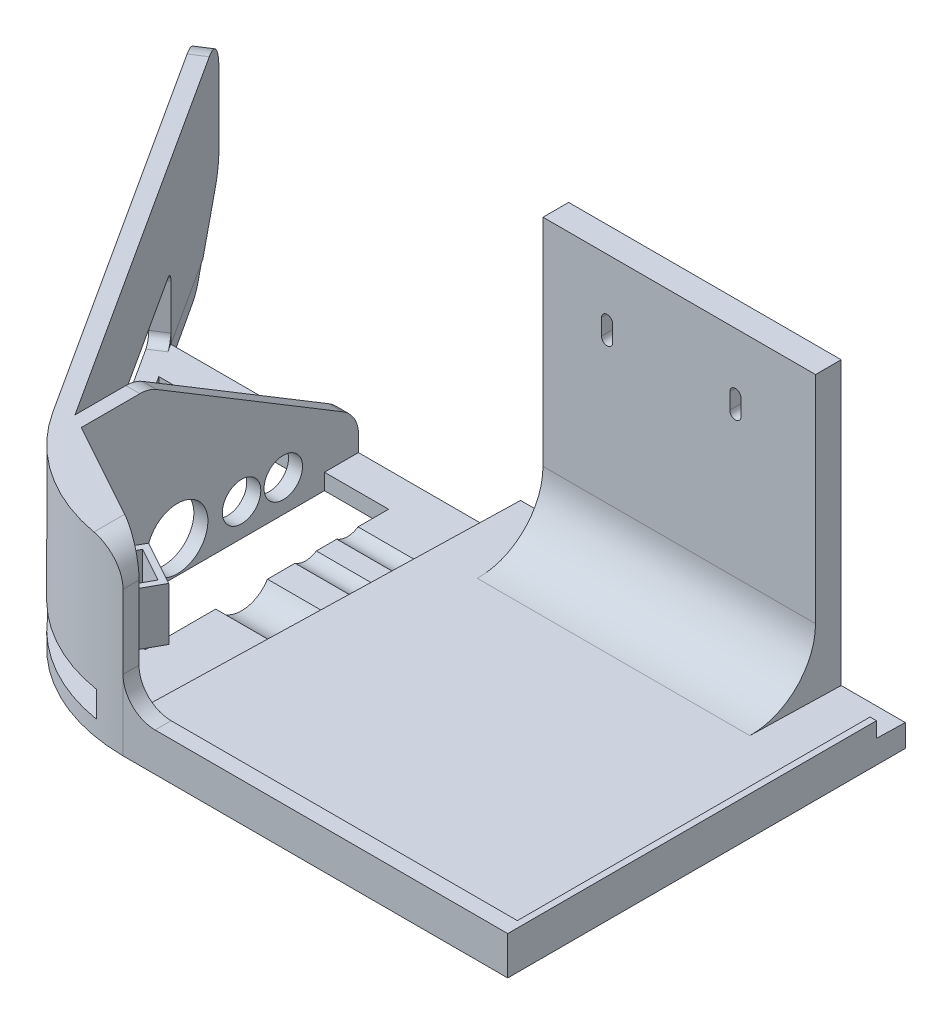
SolidWorks part; units mm, degrees
ref_plane "Front Plane" through (0, 0, 0) normal (0, 0, 1) x (1, 0, 0)
ref_plane "Top Plane" through (0, 0, 0) normal (0, 1, 0) x (1, 0, 0)
ref_plane "Right Plane" through (0, 0, 0) normal (1, 0, 0) x (0, 0, -1)
sketch "Sketch1" plane through (0, 0, 0) normal (0, 1, 0) x (1, 0, 0)
  line L0 (-48.7821, 26.8903) -> (-130, 153)
  line L1 (0, 0) -> (155, 0)
  line L2 (0, 0) -> (0, 5)
  line L3 (0, 5) -> (155, 5)
  line L4 (155, 0) -> (155, 5)
  line L5 (-130, 153) -> (-125.7963, 155.7073)
  line L6 (-125.7963, 155.7073) -> (-44.5785, 29.5976)
  line L7 (-44.5785, 29.5976) -> (-48.7821, 26.8903)
  line L8 (-44.5785, 29.5976) -> (0, 5)
  line L9 (-44.5785, 29.5976) -> (-48.7821, 26.8903)
  line L10 (0, 5) -> (0, 0)
  arc A0 (0, 0) -> (-48.7821, 26.8903) centre (0.3966, 58.4127) cw
  dimension "D1" = 130
  dimension "D3" = 150
  dimension "D4" = 58.4141
  dimension "D2" = 153
  dimension "D5" = 90
  dimension "D6" = 0
  dimension "D7" = 150
  dimension "D8" = 155
  dimension "D9" = 5
  dimension "D10" = 5
extrude "Boss-Extrude2" add sketch "Sketch1" along normal blind 55 contours L7 L6 L5 L0 | A0 L2 L8 L7 | L1 L4 L3 L2
sketch "Sketch2" plane through (0, 0, 0) normal (0, 0, 1) x (1, 0, 0)
  line L0 (0, 0) -> (155, 0) construction
  line L1 (155, 55) -> (43, 55)
  line L2 (155, 55) -> (155, 10)
  line L3 (155, 10) -> (43, 10)
  line L4 (43, 55) -> (43, 10)
  line L5 (5, 50) -> (35, 50)
  line L6 (5, 50) -> (5, 25)
  line L7 (5, 25) -> (35, 25)
  line L8 (35, 50) -> (35, 25)
  line L9 (0, 55) -> (0, 0) construction
  circle A0 centre (5, 50) radius 1.75
  circle A1 centre (35, 50) radius 1.75
  circle A2 centre (5, 25) radius 1.75
  circle A3 centre (35, 25) radius 1.75
  line M10 (155, 0) -> (155, 55)
  line M11 (155, 55) -> (0, 55)
  dimension "D6" = 3.5
  dimension "D7" = 3.5
  dimension "D8" = 3.5
  dimension "D9" = 3.5
  dimension "D2" = 25
  dimension "D3" = 25
  dimension "D4" = 30
  dimension "D5" = 5
  dimension "D10" = 10
  dimension "D11" = 8
  dimension "D12" = 8
extrude "Cut-Extrude1" cut sketch "Sketch2" against normal blind 55 contours L4 L3 M11 M10 | A2 | A0 | A1 | A3
sketch "Sketch3" plane through (-22.2397, 0, 14.3229) normal (-0.8407, 0, 0.5415) x (0.5415, 0, 0.8407)
  line L0 (-49.0207, 55) -> (-49.0207, 0) construction
  line L1 (-49.0207, 25) -> (-149.0207, 25)
  line L2 (-49.0207, 25) -> (-49.0207, 5)
  line L3 (-49.0207, 5) -> (-149.0207, 5)
  line L4 (-149.0207, 25) -> (-149.0207, 5)
  line L5 (-49.0207, 0) -> (-199.0207, 0) construction
  dimension "D1" = 5
  dimension "D2" = 20
  dimension "D3" = 100
extrude "Cut-Extrude2" cut sketch "Sketch3" against normal blind 55
sketch "Sketch4" plane through (2.115, 0, -3.833) normal (0.4831, 0, -0.8756) x (-0.8756, 0, -0.4831)
  line L6 (53.33, 25) -> (53.33, 5) construction
  line L11 (53.33, 0) -> (2.4156, 0) construction
  line L12 (8.33, 13.0659) -> (48.33, 13.0659)
  line L13 (8.33, 13.0659) -> (8.33, 5)
  line L14 (8.33, 5) -> (48.33, 5)
  line L15 (48.33, 13.0659) -> (48.33, 5)
  dimension "D1" = 5
  dimension "D2" = 40
  dimension "D3" = 5
extrude "Cut-Extrude3" cut sketch "Sketch4" against normal blind 55
sketch "Sketch5" plane through (0, 0, 0) normal (0, -1, 0) x (1, 0, 0)
  line L0 (0, -5) -> (-44.5785, -29.5976)
  line L2 (0, -5) -> (0, -155.7073)
  line L3 (0, -155.7073) -> (-125.7963, -155.7073)
  line L5 (-44.5785, -29.5976) -> (0, -5) construction
  line L6 (-44.5785, -29.5976) -> (-125.7963, -155.7073)
extrude "Boss-Extrude4" add sketch "Sketch5" against normal blind 5
sketch "Sketch8" plane through (0, 5, 0) normal (0, 1, 0) x (1, 0, 0)
  line L5 (-44.5785, 29.5976) -> (-98.7237, 113.6707)
  line L7 (-44.5785, 29.5976) -> (-44.5785, 113.6707)
  line L8 (-44.5785, 113.6707) -> (-98.7237, 113.6707)
extrude "Cut-Extrude4" cut sketch "Sketch8" against normal blind 50
sketch "Sketch9" plane through (0, 5, 0) normal (0, 1, 0) x (1, 0, 0)
  line L1 (-40.2007, 27.182) -> (-44.5785, 27.182)
  line L2 (-40.2007, 27.182) -> (-40.2007, 113.6707)
  line L3 (-40.2007, 113.6707) -> (-44.5785, 113.6707)
  line L4 (-44.5785, 27.182) -> (-44.5785, 113.6707)
extrude "Boss-Extrude7" add sketch "Sketch9" along normal blind 50
sketch "Sketch10" plane through (0, 5, 0) normal (0, 1, 0) x (1, 0, 0)
  line L1 (-40.2007, 113.6707) -> (-20.2007, 113.6707)
  line L2 (-40.2007, 113.6707) -> (-40.2007, 27.1384)
  line L3 (-40.2007, 27.1384) -> (-20.2007, 27.1384)
  line L4 (-20.2007, 113.6707) -> (-20.2007, 27.1384)
  dimension "D1" = 20
extrude "Cut-Extrude5" cut sketch "Sketch10" against normal blind 10
sketch "Sketch12" plane through (-40.2007, 0, 0) normal (1, 0, 0) x (0, 0, -1)
  line L6 (27.182, 5) -> (27.182, 13.0659) construction
  circle A0 centre (57.182, 10) radius 9.5
  circle A1 centre (77.182, 10) radius 6
  dimension "D4" = 19
  dimension "D5" = 12
  dimension "D1" = 30
  dimension "D3" = 20
extrude "Cut-Extrude6" cut sketch "Sketch12" against normal blind 10
sketch "Sketch13" plane through (-40.2007, 0, 0) normal (1, 0, 0) x (0, 0, -1)
  circle A0 centre (57.182, 10) radius 9.5
  circle A1 centre (77.182, 10) radius 6
  circle A2 centre (57.182, 10) radius 9.5 construction
  circle A3 centre (77.182, 10) radius 6 construction
  dimension "D1" = 0
  dimension "D2" = 0
  dimension "D3" = 19
  dimension "D4" = 12
extrude "Cut-Extrude7" cut sketch "Sketch13" along normal blind 50
sketch "Sketch14" plane through (0, 5, 0) normal (0, 1, 0) x (1, 0, 0)
  line L0 (0, 103.0381) -> (-91.876, 103.0381)
  line L1 (0, 155.7073) -> (-126.1063, 155.7073)
  line L2 (0, 155.7073) -> (0, 103.0381)
  line L5 (-98.7237, 113.6707) -> (-125.7963, 155.7073) construction
  line L6 (-91.876, 103.0381) -> (-126.1063, 155.7073)
extrude "Cut-Extrude8" cut sketch "Sketch14" against normal blind 50
sketch "Sketch15" plane through (-22.2397, 0, 14.3229) normal (-0.8407, 0, 0.5415) x (0.5415, 0, 0.8407)
  line L0 (-176.0359, 0) -> (-199.0207, 18.2475)
  line L1 (-199.0207, 0) -> (-176.0359, 0)
  line L2 (-199.0207, 0) -> (-199.0207, 18.2475)
extrude "Cut-Extrude9" cut sketch "Sketch15" against normal blind 50
sketch "Sketch16" plane through (-40.2007, 0, 0) normal (1, 0, 0) x (0, 0, -1)
  line L0 (113.6707, 15.4952) -> (48.2529, 55)
  line L1 (113.6707, 55) -> (113.6707, 5) construction
  line L2 (27.182, 55) -> (113.6707, 55) construction
  line L3 (48.2529, 55) -> (113.6707, 55)
  line L4 (113.6707, 55) -> (113.6707, 15.4952)
extrude "Cut-Extrude10" cut sketch "Sketch16" against normal blind 10
fillet "Fillet5" radius 3 4 edges at (-100.8476, 5, -112.3029) (-46.6803, 5, -28.2439) (-100.8255, 25, -112.3171) (-46.6803, 25, -28.2439)
sketch "Sketch18" plane through (0, 5, 0) normal (0, 1, 0) x (1, 0, 0)
  line L1 (0, 103.0381) -> (-98.7678, 103.0381)
  line L2 (0, 103.0381) -> (0, 113.6423)
  line L3 (0, 113.6423) -> (-98.7678, 113.6423)
  line L4 (-98.7678, 103.0381) -> (-98.7678, 113.6423)
extrude "Boss-Extrude8" add sketch "Sketch18" against normal blind 5
sketch "Sketch19" plane through (0, 0, 0) normal (0, -1, 0) x (1, 0, 0)
  line L0 (-97.8232, -103.0381) -> (-98.7678, -104.5048)
  line L5 (-98.7678, -104.5048) -> (-98.7678, -103.0381)
  line L6 (-98.7678, -104.5048) -> (-98.7678, -103.0381) construction
  line L7 (-98.7678, -103.0381) -> (-97.8232, -103.0381)
extrude "Cut-Extrude11" cut sketch "Sketch19" against normal blind 5 contours L0 L5 L7
sketch "Sketch20" plane through (0, 0, 0) normal (0, -1, 0) x (1, 0, 0)
  line L1 (0, -5) -> (155, -5)
  line L2 (0, -5) -> (0, -124)
  line L3 (0, -124) -> (155, -124)
  line L4 (155, -5) -> (155, -124)
  dimension "D1" = 119
  dimension "D2" = 155
extrude "Boss-Extrude9" add sketch "Sketch20" against normal blind 10
sketch "Sketch21" plane through (155, 0, 0) normal (1, 0, 0) x (0, 0, -1)
  line L1 (124, 10) -> (0, 10) construction
  line L4 (5, 10) -> (124, 10)
  line L5 (124, 10) -> (124, 7)
  line L6 (124, 7) -> (5, 10)
  line L7 (124, 10) -> (124, 0) construction
  dimension "D1" = 5
  dimension "D2" = 0
  dimension "D3" = 3
extrude "Cut-Extrude13" cut sketch "Sketch21" against normal blind 155
sketch "Sketch24" plane through (0, 0, 0) normal (0, -1, 0) x (1, 0, 0)
  line L0 (0, -124) -> (155, -124) construction
  line L1 (125, -124) -> (15, -124)
  line L2 (125, -124) -> (125, -116)
  line L3 (125, -116) -> (15, -116)
  line L4 (15, -124) -> (15, -116)
  line L5 (155, 0) -> (155, -124) construction
  dimension "D1" = 30
  dimension "D2" = 110
  dimension "D3" = 8
extrude "Boss-Extrude10" add sketch "Sketch24" against normal blind 95
fillet "Fillet6" radius 20 1 edges at (70, 7.2017, -116)
sketch "Sketch25" plane through (0, 0, -124) normal (0, 0, -1) x (-1, 0, 0)
  line L0 (-33.25, 77) -> (-33.25, 72)
  line L6 (-125, 95) -> (-15, 95) construction
  line L10 (-36.75, 77) -> (-36.75, 72)
  line L11 (-73.25, 77) -> (-73.25, 72)
  line L12 (-76.75, 77) -> (-76.75, 72)
  line L13 (-15, 95) -> (-15, 27.7122) construction
  arc A4 (-36.75, 77) -> (-33.25, 77) centre (-35, 77) cw
  arc A5 (-73.25, 72) -> (-76.75, 72) centre (-75, 72) cw
  arc A6 (-73.25, 77) -> (-76.75, 77) centre (-75, 77) ccw
  arc A7 (-36.75, 72) -> (-33.25, 72) centre (-35, 72) ccw
  arc A8 (-33.25, 77) -> (-36.75, 77) centre (-35, 77) ccw
  point P11 (0, 0)
  dimension "D4" = 40
  dimension "D5" = 20
  dimension "D6" = 40
  dimension "D7" = 20
  dimension "D1" = 23
  dimension "D2" = 23
  dimension "D3" = 5
sketch "Sketch26" plane through (2.115, 0, -3.833) normal (0.4831, 0, -0.8756) x (-0.8756, 0, -0.4831)
  line L0 (48.33, 13.0659) -> (8.33, 13.0659) construction
  line L1 (36.33, 13.0659) -> (20.33, 13.0659)
  line L2 (36.33, 13.0659) -> (36.33, 14.5659)
  line L3 (36.33, 14.5659) -> (20.33, 14.5659)
  line L4 (20.33, 13.0659) -> (20.33, 14.5659)
  line L5 (8.33, 13.0659) -> (8.33, 5) construction
  line L6 (48.33, 55) -> (48.33, 13.0659) construction
  dimension "D1" = 12
  dimension "D2" = 12
  dimension "D3" = 16
  dimension "D4" = 1.5
extrude "Boss-Extrude11" add sketch "Sketch26" along normal blind 12
sketch "Sketch27" plane through (0, 14.5659, 0) normal (0, 1, 0) x (1, 0, 0)
  line L0 (-15.6851, 13.6547) -> (-9.8877, 24.1614)
  line L1 (-9.8877, 24.1614) -> (-23.8966, 31.8913)
  line L2 (-23.8966, 31.8913) -> (-29.694, 21.3846)
  line L3 (-29.694, 21.3846) -> (-28.0304, 20.4667)
  line L4 (-29.694, 21.3846) -> (-15.6851, 13.6547) construction
  line L5 (-28.0304, 20.4667) -> (-23.151, 29.3098)
  line L6 (-23.151, 29.3098) -> (-12.4692, 23.4158)
  line L7 (-12.4692, 23.4158) -> (-17.3486, 14.5727)
  line L8 (-17.3486, 14.5727) -> (-15.6851, 13.6547)
  dimension "D1" = 1.9
  dimension "D2" = 1.9
  dimension "D3" = 1.9
extrude "Boss-Extrude12" add sketch "Sketch27" along normal blind 15
sketch "Sketch28" plane through (0, 14.5659, 0) normal (0, 1, 0) x (1, 0, 0)
  circle A0 centre (-20.2498, 21.9412) radius 2.5
  dimension "D1" = 5
extrude "Cut-Extrude15" cut sketch "Sketch28" against normal blind 5
extrude "Cut-Extrude17" cut sketch "Sketch25" against normal blind 35 contours L10 A7 L0 A4 | L11 A6 L12 A5
sketch "Sketch29" plane through (0, 0, 0) normal (0, 0, 1) x (1, 0, 0)
  line L1 (43, 55) -> (0, 55)
  line L6 (0, 12) -> (43, 12)
  line L7 (0, 12) -> (0, 55)
  line L8 (43, 55) -> (43, 12)
extrude "Cut-Extrude18" cut sketch "Sketch29" against normal blind 35
fillet "Fillet9" radius 10 5 edges at (-127.8982, 55, -154.3536) (-115.5221, 0, -134.985) (-127.8982, 18.2475, -154.3536) (-42.3896, 15.4952, -113.6707) (-42.3896, 55, -48.2529)
sketch "Sketch31" plane through (155, 0, 0) normal (1, 0, 0) x (0, 0, -1)
  line L0 (124, 7) -> (124, 0) construction
  line L1 (0, 0) -> (124, 0)
  line L2 (0, 0) -> (0, 12)
  line L3 (0, 12) -> (124, 12)
  line L4 (124, 0) -> (124, 12)
  dimension "D1" = 0
  dimension "D2" = 12
extrude "Boss-Extrude14" add sketch "Sketch31" against normal blind 2
sketch "Sketch32" plane through (153, 0, 0) normal (-1, 0, 0) x (0, 0, 1)
  line L0 (-124, 12) -> (0, 12) construction
  line L1 (0, 10) -> (-5, 10)
  line L2 (0, 10) -> (0, 12)
  line L3 (0, 12) -> (-5, 12)
  line L4 (-5, 10) -> (-5, 12)
  dimension "D1" = 5
  dimension "D2" = 2
extrude "Boss-Extrude15" add sketch "Sketch32" along normal blind 132
sketch "Sketch33" plane through (0, 0, 0) normal (0, 0, 1) x (1, 0, 0)
  line L0 (0, 0) -> (155, 0) construction
  line L1 (155, 12) -> (135, 12)
  line L2 (155, 12) -> (155, 0)
  line L3 (155, 0) -> (135, 0)
  line L4 (135, 12) -> (135, 0)
  dimension "D1" = 20
extrude "Cut-Extrude19" cut sketch "Sketch33" against normal blind 160
sketch "Sketch34" plane through (0, 0, 0) normal (0, 0, 1) x (1, 0, 0)
  line L0 (0, 0) -> (135, 0) construction
  line L1 (135, 12) -> (133, 12)
  line L2 (135, 12) -> (135, 0)
  line L3 (135, 0) -> (133, 0)
  line L4 (133, 12) -> (133, 0)
  dimension "D1" = 2
extrude "Boss-Extrude17" add sketch "Sketch34" against normal blind 123
sketch "Sketch36" plane through (-40.2007, 0, 0) normal (1, 0, 0) x (0, 0, -1)
  line L0 (103.0381, 0) -> (27.1384, 0) construction
  circle A0 centre (90.1949, 10) radius 6
  dimension "D1" = 12
  dimension "D2" = 10
extrude "Cut-Extrude20" cut sketch "Sketch36" against normal mid plane 80
sketch "Sketch38" plane through (125, 0, 0) normal (1, 0, 0) x (0, 0, -1)
  line L0 (95.496, 7.7186) -> (124, 7)
  line L1 (124, 7) -> (124, 95)
  line L2 (124, 95) -> (116, 95)
  line L3 (116, 95) -> (95.496, 7.7186)
extrude "Cut-Extrude21" cut sketch "Sketch38" against normal blind 25
sketch "Sketch39" plane through (0, 0, 0) normal (0, 0, 1) x (1, 0, 0)
  line L0 (0, 0) -> (135, 0) construction
  line L1 (135, 12) -> (120, 12)
  line L2 (135, 12) -> (135, 0)
  line L3 (135, 0) -> (120, 0)
  line L4 (120, 12) -> (120, 0)
  dimension "D1" = 15
extrude "Cut-Extrude22" cut sketch "Sketch39" against normal blind 165
fillet "Fillet10" radius 10 2 edges at (0, 12, -2.5) (0, 55, -2.5)
sketch "Sketch40" plane through (0, 0, 0) normal (0, 0, 1) x (1, 0, 0)
  line L6 (0, 0) -> (120, 0) construction
  line L7 (120, 12) -> (118, 12)
  line L8 (120, 12) -> (120, 0)
  line L9 (120, 0) -> (118, 0)
  line L10 (118, 12) -> (118, 0)
  dimension "D1" = 2
extrude "Boss-Extrude18" add sketch "Sketch40" against normal blind 115
